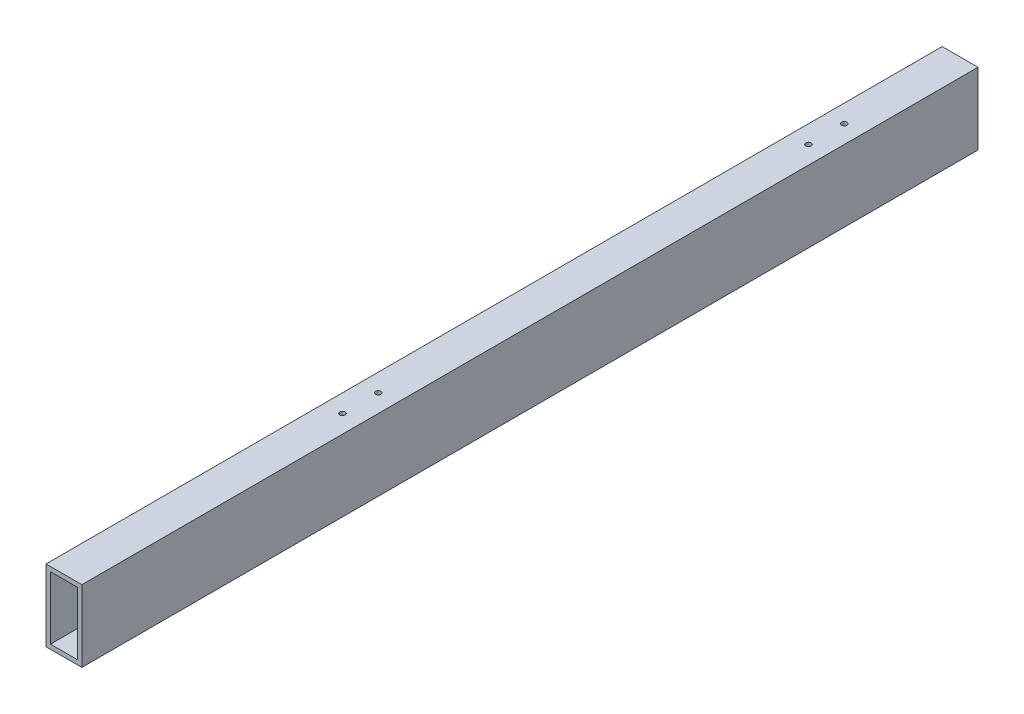
SolidWorks part; units mm, degrees
material "6061-T4 (SS)"
ref_plane "Front Plane" through (0, 0, 0) normal (0, 0, 1) x (1, 0, 0)
ref_plane "Top Plane" through (0, 0, 0) normal (0, 1, 0) x (1, 0, 0)
ref_plane "Right Plane" through (0, 0, 0) normal (1, 0, 0) x (0, 0, -1)
sketch "Sketch1" plane through (0, 0, 0) normal (0, 0, 1) x (1, 0, 0)
  line L0 (-9.525, 22.225) -> (9.525, 22.225)
  line L1 (-12.7, 25.4) -> (12.7, 25.4)
  line L2 (-12.7, 25.4) -> (-12.7, -25.4)
  line L3 (-12.7, -25.4) -> (12.7, -25.4)
  line L4 (12.7, 25.4) -> (12.7, -25.4)
  line L5 (-12.7, 25.4) -> (12.7, -25.4) construction
  line L6 (-12.7, -25.4) -> (12.7, 25.4) construction
  line L7 (9.525, 22.225) -> (9.525, -22.225)
  line L8 (-9.525, -22.225) -> (9.525, -22.225)
  line L9 (-9.525, 22.225) -> (-9.525, -22.225)
  point P0 (0, 0)
  dimension "D1" = 50.8
  dimension "D2" = 25.4
  dimension "D3" = 3.175
extrude "Boss-Extrude1" add sketch "Sketch1" along normal mid plane 635
sketch "Sketch2" plane through (0, 25.4, 0) normal (0, 1, 0) x (1, 0, 0)
  line L0 (12.7, -317.5) -> (-12.7, -317.5) construction
  line L1 (-12.7, -317.5) -> (-12.7, 317.5) construction
  line L2 (12.7, 317.5) -> (-12.7, 317.5) construction
  line L3 (12.7, -317.5) -> (12.7, 317.5) construction
  circle A0 centre (0, -120.1166) radius 1.905
  circle A1 centre (0, -94.7166) radius 1.905
  circle A2 centre (0, 235.4859) radius 1.905
  circle A3 centre (0, 210.0859) radius 1.905
  dimension "D1" = 3.81
  dimension "D2" = 197.3834
  dimension "D3" = 12.7
  dimension "D4" = 25.4
  dimension "D5" = 12.7
  dimension "D6" = 82.0141
  dimension "D7" = 12.7
  dimension "D8" = 25.4
extrude "Cut-Extrude1" cut sketch "Sketch2" against normal through all
